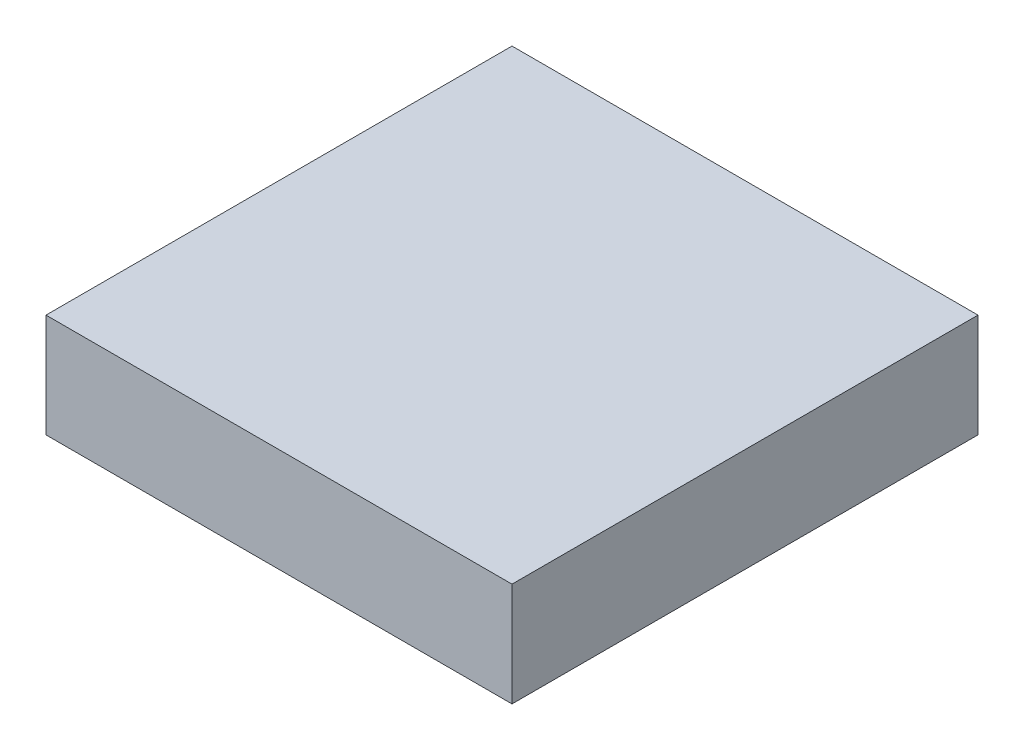
SolidWorks part; units mm, degrees
ref_plane "Front Plane" through (0, 0, 0) normal (0, 0, 1) x (1, 0, 0)
ref_plane "Top Plane" through (0, 0, 0) normal (0, 1, 0) x (1, 0, 0)
ref_plane "Right Plane" through (0, 0, 0) normal (1, 0, 0) x (0, 0, -1)
sketch "Sketch1" plane through (0, 0, 0) normal (0, 1, 0) x (1, 0, 0)
  line L1 (-49.2103, 373.03) -> (357.1897, 373.03)
  line L2 (-49.2103, 373.03) -> (-49.2103, -33.37)
  line L3 (-49.2103, -33.37) -> (357.1897, -33.37)
  line L4 (357.1897, 373.03) -> (357.1897, -33.37)
extrude "Boss-Extrude1" add sketch "Sketch1" along normal blind 90.4875
